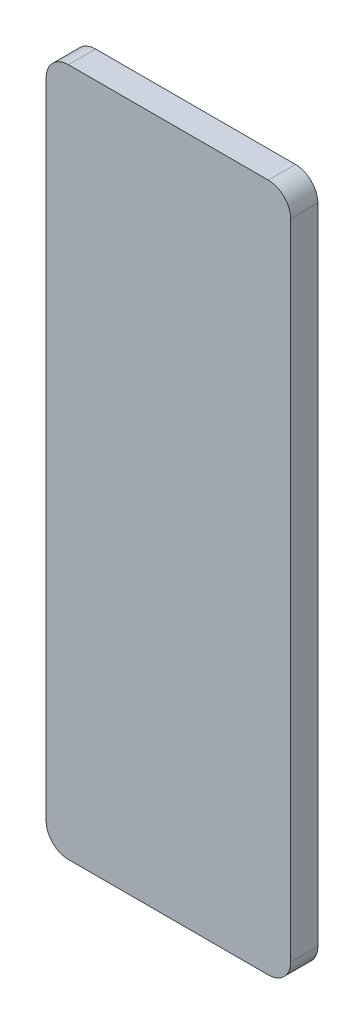
SolidWorks part; units mm, degrees
ref_plane "前视基准面" through (0, 0, 0) normal (0, 0, 1) x (1, 0, 0)
ref_plane "上视基准面" through (0, 0, 0) normal (0, 1, 0) x (1, 0, 0)
ref_plane "右视基准面" through (0, 0, 0) normal (1, 0, 0) x (0, 0, -1)
other "Configuration Table"
sketch "草图1" plane through (0, 0, 0) normal (0, 0, 1) x (1, 0, 0)
  line L1 (-0.675, 1.9) -> (0.675, 1.9)
  line L2 (-0.675, 1.9) -> (-0.675, -1.9)
  line L3 (-0.675, -1.9) -> (0.675, -1.9)
  line L4 (0.675, 1.9) -> (0.675, -1.9)
  line L5 (-0.675, 1.9) -> (0.675, -1.9) construction
  line L6 (-0.675, -1.9) -> (0.675, 1.9) construction
  point P0 (0, 0)
  dimension "D1" = 1.35
  dimension "D2" = 3.8
extrude "凸台-拉伸1" add sketch "草图1" along normal blind 0.15
fillet "圆角1" radius 0.1233 4 edges at (0.675, -1.9, 0.075) (-0.675, -1.9, 0.075) (-0.675, 1.9, 0.075) (0.675, 1.9, 0.075)
equation "\"L\"= 4.1mm'长度"
equation "\"W\"= 4.1mm'宽度"
equation "\"E\"= 1.35mm'引脚长度"
equation "\"T\"= 3.0mm'高度"
equation "\"F\"= \"T\"/20'引脚厚度"
equation "\"D1@草图1\"=\"E\""
equation "\"D2@草图1\"=\"W\"-2*\"F\""
equation "\"D1@凸台-拉伸1\"=\"F\""
equation "\"D1@圆角1\"=\"W\"/15-\"F\""
